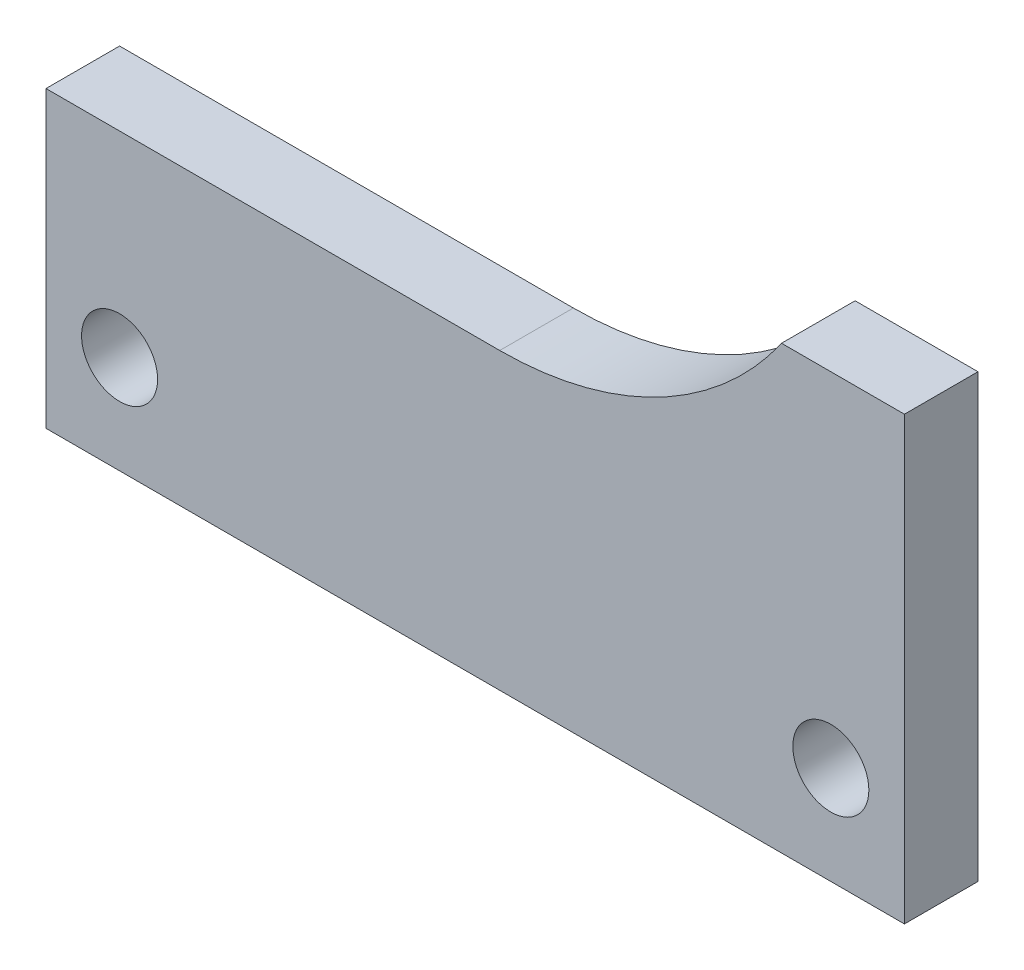
SolidWorks part; units mm, degrees
ref_plane "Front Plane" through (0, 0, 0) normal (0, 0, 1) x (1, 0, 0)
ref_plane "Top Plane" through (0, 0, 0) normal (0, 1, 0) x (1, 0, 0)
ref_plane "Right Plane" through (0, 0, 0) normal (1, 0, 0) x (0, 0, -1)
sketch "Sketch1" plane through (0, 0, 0) normal (0, 0, 1) x (1, 0, 0)
  line L0 (46.5738, 8.8877) -> (45.063, 8.8877)
  line L1 (33.5738, 2.8877) -> (15.0738, 2.8877)
  line L2 (15.0738, 2.8877) -> (15.0738, 0.8877)
  line L3 (15.0738, 0.8877) -> (15.0738, -1.1123)
  line L4 (15.0738, -1.1123) -> (15.0738, -9.1123)
  line L5 (15.0738, -9.1123) -> (50.0738, -9.1123)
  line L6 (50.0738, -9.1123) -> (50.0738, 8.8877)
  line L7 (50.0738, 8.8877) -> (48.5738, 8.8877)
  line L8 (46.5738, 8.8877) -> (48.5738, 8.8877)
  line L9 (18.0738, -5.1123) -> (47.0738, -5.1123) construction
  arc A0 (33.5738, 2.8877) -> (45.063, 8.8877) centre (33.5738, 16.8877) ccw
  circle A1 centre (18.0738, -5.1123) radius 1.55
  circle A2 centre (47.0738, -5.1123) radius 1.55
  spline S0 degree 3 poles (15.0738, 0.8877) (18.0027, 0.8885) (23.213, 0.8859) (29.3356, 0.8746) (34.0145, 0.8611) (37.2077, 0.8512) (39.4215, 0.8483) (40.7033, 0.8511) (41.5923, 0.8586) (42.3668, 0.8682) (42.8402, 0.9057) (43.3979, 1.0101) (43.931, 1.1723) (44.6969, 1.5737) (45.3907, 2.1236) (46.1338, 3.0143) (46.5493, 3.8732) (46.5791, 4.8299) (46.5496, 5.8386) (46.5734, 7.0399) (46.5768, 7.9698) (46.5738, 8.8877) knots 0 0 0 0 0.062498 0.124998 0.187498 0.249998 0.296873 0.343748 0.36563 0.390623 0.437498 0.440805 0.484373 0.531248 0.578123 0.624998 0.717206 0.749998 0.77658 0.874998 0.999998 0.999998 0.999998 0.999998 weights 0.5 0.5 0.5 0.5 0.5 0.5 0.5 0.5 0.5 0.5 0.5 0.5 0.5 0.5 0.5 0.5 0.5 0.5 0.5 0.5 0.5 0.5 construction
  spline S1 degree 3 poles (48.5738, 8.8877) (48.5709, 7.9418) (48.5572, 6.962) (48.5842, 5.9825) (48.5805, 4.7967) (48.4783, 3.474) (47.877, 1.9356) (46.7849, 0.6785) (45.7961, -0.1116) (44.7091, -0.6848) (43.8906, -0.9317) (43.0764, -1.0856) (42.4264, -1.1314) (41.6045, -1.1421) (40.7161, -1.1485) (39.4194, -1.152) (37.2027, -1.1488) (34.0079, -1.139) (29.3307, -1.1254) (23.2105, -1.1141) (18.0019, -1.1115) (15.0738, -1.1123) knots 0 0 0 0 0.125 0.223418 0.25 0.282792 0.375 0.421875 0.46875 0.515625 0.559193 0.5625 0.609375 0.634368 0.65625 0.703125 0.75 0.8125 0.875 0.9375 1 1 1 1 weights 0.5 0.5 0.5 0.5 0.5 0.5 0.5 0.5 0.5 0.5 0.5 0.5 0.5 0.5 0.5 0.5 0.5 0.5 0.5 0.5 0.5 0.5 construction
  dimension "D6" = 14
  dimension "D11" = 3.1
  dimension "D12" = 4
  dimension "D14" = 3
  dimension "D1" = 8
  dimension "D2" = 2
  dimension "D3" = 12
  dimension "D4" = 18
  dimension "D5" = 35
  dimension "D7" = 14
  dimension "D8" = 16.5
  dimension "D9" = 1.5
  dimension "D10" = 2
  dimension "D13" = 3
extrude "Boss-Extrude1" add sketch "Sketch1" along normal blind 3
